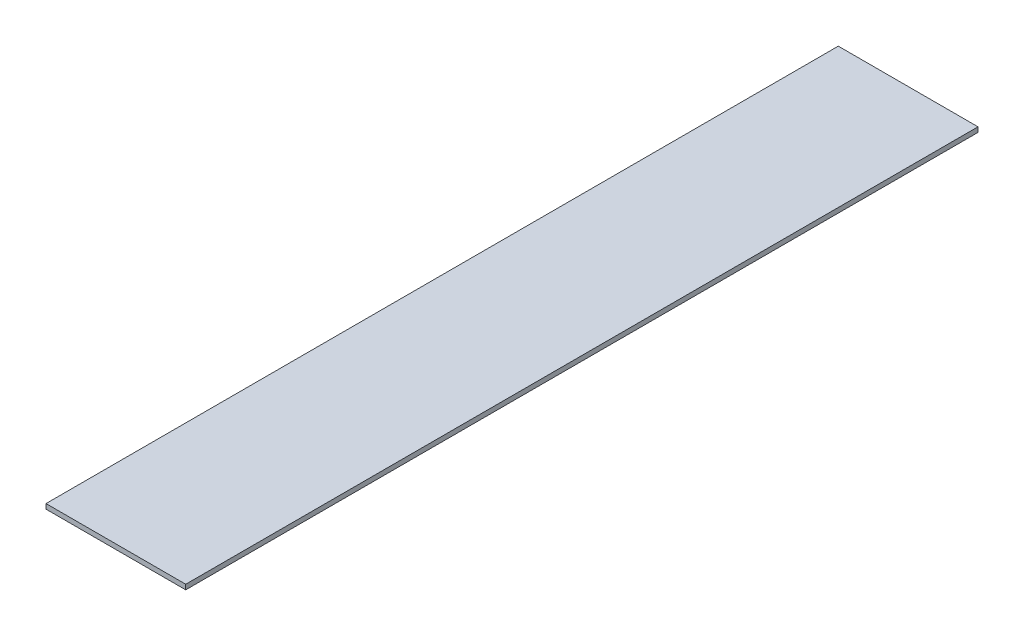
SolidWorks part; units mm, degrees
ref_plane "Front Plane" through (0, 0, 0) normal (0, 0, 1) x (1, 0, 0)
ref_plane "Top Plane" through (0, 0, 0) normal (0, 1, 0) x (1, 0, 0)
ref_plane "Right Plane" through (0, 0, 0) normal (1, 0, 0) x (0, 0, -1)
sketch "Sketch2" plane through (0, 0, 0) normal (0, 1, 0) x (1, 0, 0)
  line L1 (-64.37, 365) -> (64.37, 365)
  line L2 (-64.37, 365) -> (-64.37, -365)
  line L3 (-64.37, -365) -> (64.37, -365)
  line L4 (64.37, 365) -> (64.37, -365)
  dimension "D1" = 128.74
  dimension "D2" = 64.37
  dimension "D3" = 730
  dimension "D4" = 365
extrude "Boss-Extrude1" add sketch "Sketch2" along normal blind 4.5
